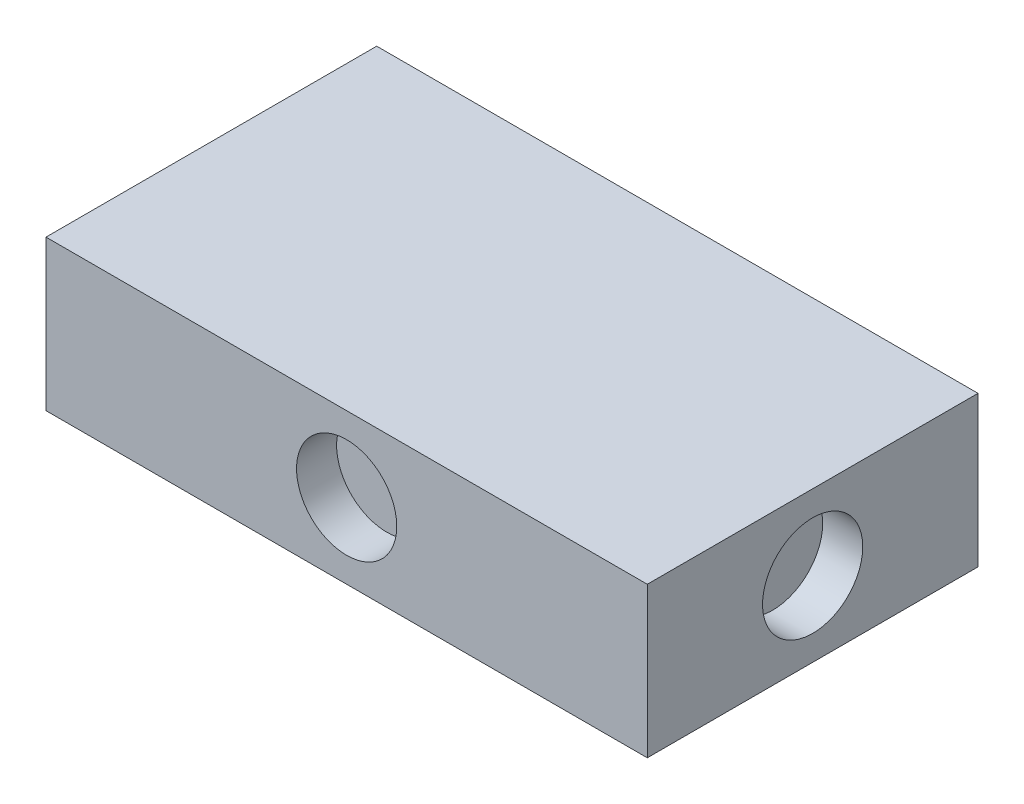
SolidWorks part; units mm, degrees
material "Polyurethane Foam Rigid"
ref_plane "Front Plane" through (0, 0, 0) normal (0, 0, 1) x (1, 0, 0)
ref_plane "Top Plane" through (0, 0, 0) normal (0, 1, 0) x (1, 0, 0)
ref_plane "Right Plane" through (0, 0, 0) normal (1, 0, 0) x (0, 0, -1)
sketch "Sketch1" plane through (0, 0, 0) normal (0, 1, 0) x (1, 0, 0)
  line L1 (-38.1, -20.955) -> (38.1, -20.955)
  line L2 (-38.1, -20.955) -> (-38.1, 20.955)
  line L3 (-38.1, 20.955) -> (38.1, 20.955)
  line L4 (38.1, -20.955) -> (38.1, 20.955)
  line L5 (-38.1, -20.955) -> (38.1, 20.955) construction
  line L6 (-38.1, 20.955) -> (38.1, -20.955) construction
  point P0 (0, 0)
  dimension "D1" = 41.91
  dimension "D2" = 76.2
extrude "Boss-Extrude1" add sketch "Sketch1" along normal blind 19.05
sketch "Sketch2" plane through (0, 0, 20.955) normal (0, 0, 1) x (1, 0, 0)
  line L0 (38.1, 19.05) -> (38.1, 0) construction
  circle A0 centre (0, 9.525) radius 6.35
  point P4 (38.1, 9.525)
  dimension "D1" = 12.7
sketch "Sketch3" plane through (0, 0, -20.955) normal (0, 0, -1) x (-1, 0, 0)
  circle A0 centre (0, 9.525) radius 6.35
  dimension "D1" = 12.7
sketch "Sketch4" plane through (-38.1, 0, 0) normal (-1, 0, 0) x (0, 0, 1)
  line L1 (-20.955, 19.05) -> (-20.955, 0) construction
  circle A0 centre (0, 9.525) radius 6.35
  point P6 (-20.955, 9.525)
  dimension "D1" = 12.7
sketch "Sketch5" plane through (38.1, 0, 0) normal (1, 0, 0) x (0, 0, -1)
  circle A0 centre (0, 9.525) radius 6.35
  dimension "D1" = 12.7
extrude "Cut-Extrude1" cut sketch "Sketch5" against normal blind 5.08
extrude "Cut-Extrude2" cut sketch "Sketch2" against normal blind 5.08 contours A0
extrude "Cut-Extrude3" cut sketch "Sketch3" against normal blind 5.08 contours A0
extrude "Cut-Extrude4" cut sketch "Sketch4" against normal blind 5.08 contours A0
